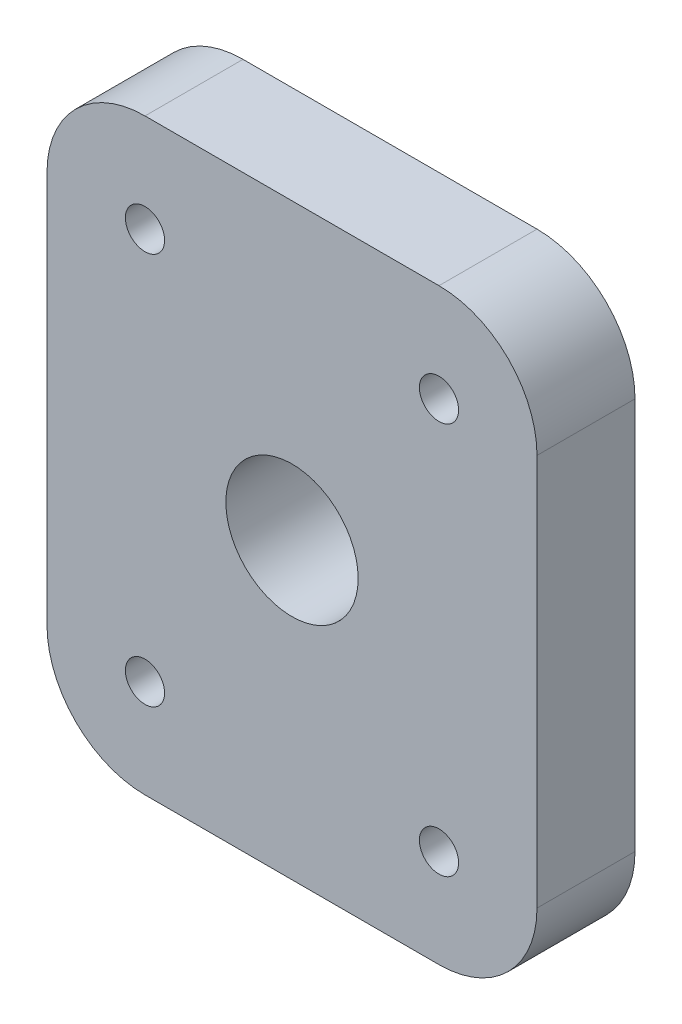
SolidWorks part; units mm, degrees
ref_plane "Front Plane" through (0, 0, 0) normal (0, 0, 1) x (1, 0, 0)
ref_plane "Top Plane" through (0, 0, 0) normal (0, 1, 0) x (1, 0, 0)
ref_plane "Right Plane" through (0, 0, 0) normal (1, 0, 0) x (0, 0, -1)
sketch "Model" plane through (0, 0, 0) normal (0, 0, 1) x (1, 0, 0)
  line L0 (106.9106, 50) -> (106.9106, 10)
  line L1 (146.9106, 60) -> (116.9106, 60)
  line L2 (156.9106, 10) -> (156.9106, 50)
  line L3 (116.9106, 0) -> (146.9106, 0)
  circle A0 centre (131.9106, 30) radius 6.75
  circle A1 centre (146.9106, 10) radius 2
  circle A2 centre (146.9106, 50) radius 2
  circle A3 centre (116.9106, 50) radius 2
  circle A4 centre (116.9106, 10) radius 2
  arc A5 (116.9106, 60) -> (106.9106, 50) centre (116.9106, 50) ccw
  arc A6 (156.9106, 50) -> (146.9106, 60) centre (146.9106, 50) ccw
  arc A7 (146.9106, 0) -> (156.9106, 10) centre (146.9106, 10) ccw
  arc A8 (106.9106, 10) -> (116.9106, 0) centre (116.9106, 10) ccw
extrude "Boss-Extrude1" add sketch "Model" along normal blind 10
sketch "Sketch2" plane through (0, 0, 10) normal (0, 0, 1) x (1, 0, 0)
  text T0 "Copyright © Adarsh Belavatagi and Manikanta Pujar 2018.\r\nThis documentation describes Open Hardware and is licensed under the CERN OHL v. 1.2.\r\nYou may redistribute and modify this documentation under the terms of the CERN OHL v.1.2. \r\n(http://ohwr.org/cernohl). This documentation is distributed WITHOUT ANY EXPRESS OR\r\nIMPLIED WARRANTY, INCLUDING OF MERCHANTABILITY, SATISFACTORY QUALITY AND FITNESS FOR A PARTICULAR PURPOSE.\r\nPlease see the CERN OHL v.1.2 for applicable conditions\r\n\r\nThe full text of the license is available in LICENSE.txt(https://github.com/AdarshBelavatagi/Maudslay/blob/master/LICENSE.txt)"
